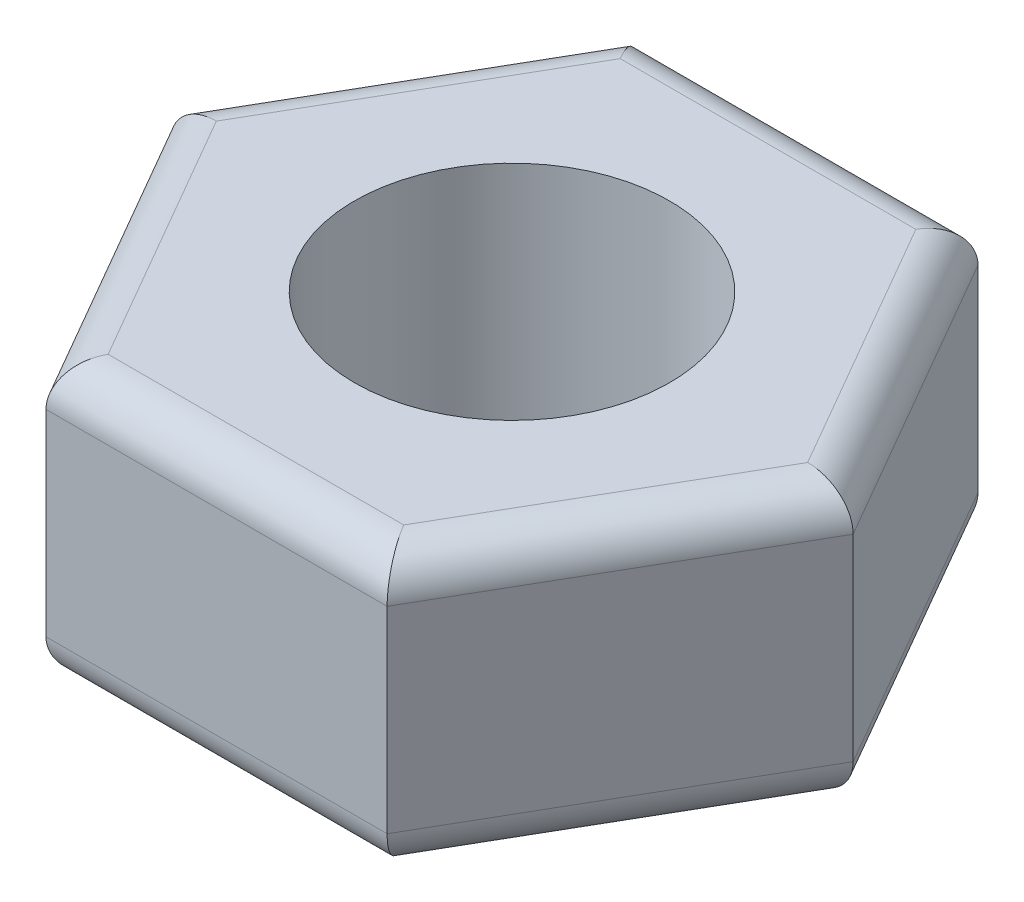
SolidWorks part; units mm, degrees
ref_plane "Front Plane" through (0, 0, 0) normal (0, 0, 1) x (1, 0, 0)
ref_plane "Top Plane" through (0, 0, 0) normal (0, 1, 0) x (1, 0, 0)
ref_plane "Right Plane" through (0, 0, 0) normal (1, 0, 0) x (0, 0, -1)
sketch "Sketch1" plane through (0, 0, 0) normal (0, 1, 0) x (1, 0, 0)
  line L1 (2.1651, 3.75) -> (-2.1651, 3.75)
  line L2 (-2.1651, 3.75) -> (-4.3301, 0)
  line L3 (-4.3301, 0) -> (-2.1651, -3.75)
  line L4 (-2.1651, -3.75) -> (2.1651, -3.75)
  line L5 (2.1651, -3.75) -> (4.3301, 0)
  line L6 (4.3301, 0) -> (2.1651, 3.75)
  circle A0 centre (0, 0) radius 3.75 construction
  circle A1 centre (0, 0) radius 2
  dimension "D2" = 4
  dimension "D1" = 7.5
extrude "Boss-Extrude1" add sketch "Sketch1" along normal blind 3.5
fillet "Fillet1" radius 0.5 12 edges at (-3.2476, 0, 1.875) (-3.2476, 0, -1.875) (0, 0, -3.75) (3.2476, 0, -1.875) (3.2476, 0, 1.875) (0, 0, 3.75) (-3.2476, 3.5, 1.875) (-3.2476, 3.5, -1.875) (3.2476, 3.5, -1.875) (0, 3.5, -3.75) (3.2476, 3.5, 1.875) (0, 3.5, 3.75)
